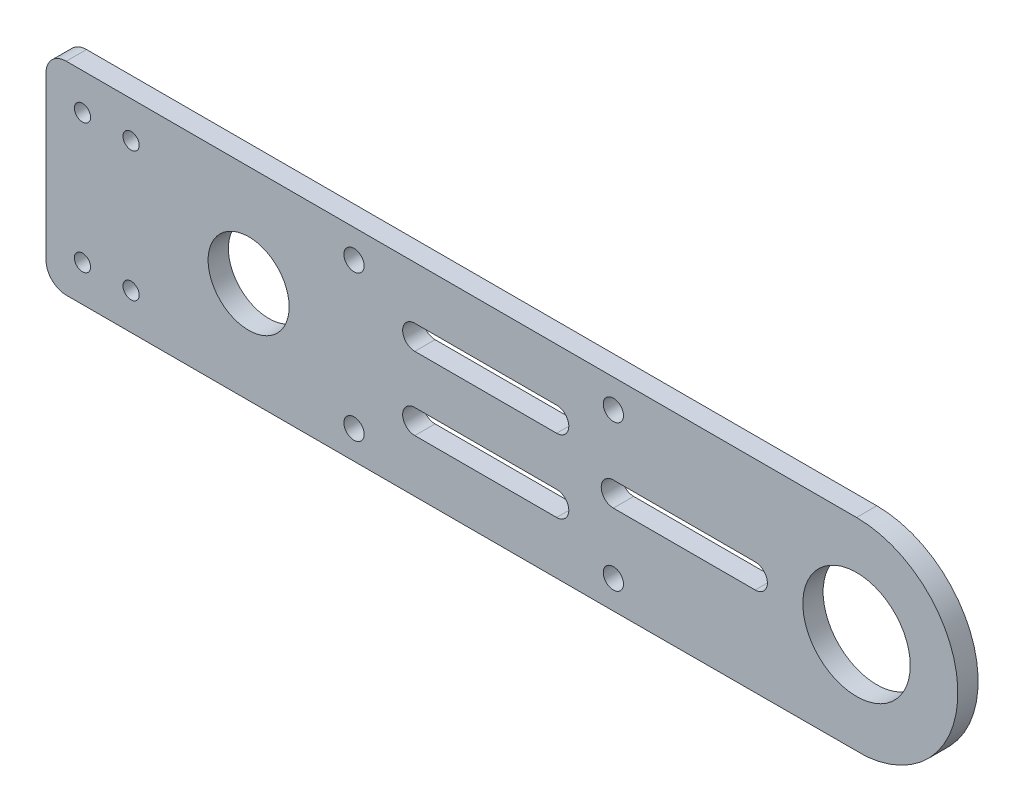
SolidWorks part; units mm, degrees
other "标注1"
sketch "草图2" plane through (-16, 25, 5) normal (-0.2141, 0.5303, 0.8203) x (0.969, 0.0095, 0.2468)
material "6061 合金"
ref_plane "前视基准面" through (0, 0, 0) normal (0, 0, 1) x (1, 0, 0)
ref_plane "上视基准面" through (0, 0, 0) normal (0, 1, 0) x (1, 0, 0)
ref_plane "右视基准面" through (0, 0, 0) normal (1, 0, 0) x (0, 0, -1)
sketch "草图1" plane through (0, 0, 0) normal (0, 0, 1) x (1, 0, 0)
  line L1 (0, 0) -> (184, 0) construction
  line L3 (75, 9) -> (110, 9) construction
  line L4 (0, 25) -> (124.8693, 25)
  line L17 (0, -25) -> (124.8693, -25)
  line L21 (0, 0) -> (5, 0) construction
  line L22 (5, 0) -> (5, 16) construction
  line L23 (124.8693, 25) -> (184, 25)
  line L24 (124.8693, -25) -> (186.4905, -24.8756)
  line L53 (75, 12) -> (110, 12)
  line L54 (75, 6) -> (110, 6)
  line L55 (75, -9) -> (110, -9) construction
  line L56 (75, -12) -> (110, -12)
  line L72 (130.7557, 4.1147) -> (130.7557, 16.1147) construction
  line L73 (130.7557, 16.1147) -> (160.7557, 16.1147) construction
  line L74 (160.7557, 16.1147) -> (130.7557, 4.1147) construction
  line L78 (130.7557, 4.1147) -> (158.292, 4.1147) construction
  line L79 (144.7181, 4.1147) -> (160.7557, 10.5297) construction
  line L80 (144.7181, 4.1147) -> (160.7557, 4.1147) construction
  line L81 (160.7557, 4.1147) -> (160.7557, 10.5297) construction
  line L91 (130.7557, 17.1147) -> (160.7557, 17.1147) construction
  line L92 (129.7557, 16.1147) -> (129.7557, 4.1147) construction
  line L93 (131.1271, 3.1862) -> (161.1271, 15.1862) construction
  line L94 (144.4708, -5.0836) -> (160.5084, -11.4986) construction
  line L95 (144.7181, 3.1147) -> (160.7557, 3.1147) construction
  line L96 (161.7557, 10.5297) -> (161.7557, 4.1147) construction
  line L97 (144.4708, 5.0836) -> (160.5084, 11.4986) construction
  line L98 (161.7557, -10.5297) -> (161.7557, -4.1147) construction
  line L99 (144.7181, -3.1147) -> (160.7557, -3.1147) construction
  line L100 (130.7557, -17.1147) -> (160.7557, -17.1147) construction
  line L101 (131.1271, -3.1862) -> (161.1271, -15.1862) construction
  line L102 (129.7557, -16.1147) -> (129.7557, -4.1147) construction
  line L103 (75, -6) -> (110, -6)
  line L104 (124, 0) -> (159, 0) construction
  line L105 (124, 3) -> (159, 3)
  line L106 (124, -3) -> (159, -3)
  line L107 (0, 25) -> (-16, 25)
  line L108 (-16, 25) -> (-16, -25)
  line L109 (-16, -25) -> (0, -25)
  line L110 (5, 16) -> (-7, 16) construction
  circle A5 centre (184, 0) radius 13.25
  circle A6 centre (184, 0) radius 16 construction
  arc A7 (186.4905, -24.8756) -> (184, 25) centre (184, 0) ccw
  circle A15 centre (5, 16) radius 2
  circle A16 centre (5, -16) radius 2
  circle A35 centre (60, 18) radius 2.5
  circle A36 centre (124, 18) radius 2.5
  circle A39 centre (34, 0) radius 10
  circle A45 centre (124, -18) radius 2.5
  circle A46 centre (60, -18) radius 2.5
  arc A80 (130.7557, 17.1147) -> (129.7557, 16.1147) centre (130.7557, 16.1147) ccw construction
  arc A81 (129.7557, 4.1147) -> (131.1271, 3.1862) centre (130.7557, 4.1147) ccw construction
  arc A82 (161.1271, 15.1862) -> (160.7557, 17.1147) centre (160.7557, 16.1147) ccw construction
  arc A83 (161.7557, 10.5297) -> (160.5084, 11.4986) centre (160.7557, 10.5297) ccw construction
  arc A84 (160.7557, 3.1147) -> (161.7557, 4.1147) centre (160.7557, 4.1147) ccw construction
  arc A85 (144.4708, 5.0836) -> (144.7181, 3.1147) centre (144.7181, 4.1147) ccw construction
  arc A86 (144.4708, -5.0836) -> (144.7181, -3.1147) centre (144.7181, -4.1147) cw construction
  arc A87 (161.7557, -10.5297) -> (160.5084, -11.4986) centre (160.7557, -10.5297) cw construction
  arc A88 (160.7557, -3.1147) -> (161.7557, -4.1147) centre (160.7557, -4.1147) cw construction
  arc A89 (130.7557, -17.1147) -> (129.7557, -16.1147) centre (130.7557, -16.1147) cw construction
  arc A90 (161.1271, -15.1862) -> (160.7557, -17.1147) centre (160.7557, -16.1147) cw construction
  arc A91 (129.7557, -4.1147) -> (131.1271, -3.1862) centre (130.7557, -4.1147) cw construction
  circle A92 centre (184, 16) radius 1.5 construction
  circle A93 centre (200, 0) radius 1.5 construction
  circle A94 centre (184, -16) radius 1.5 construction
  circle A95 centre (168, 0) radius 1.5 construction
  arc A96 (75, 12) -> (75, 6) centre (75, 9) ccw
  arc A97 (110, 6) -> (110, 12) centre (110, 9) ccw
  arc A98 (75, -12) -> (75, -6) centre (75, -9) cw
  arc A99 (110, -6) -> (110, -12) centre (110, -9) cw
  arc A100 (124, 3) -> (124, -3) centre (124, 0) ccw
  arc A101 (159, -3) -> (159, 3) centre (159, 0) ccw
  circle A102 centre (-7, 16) radius 2
  circle A103 centre (-7, -16) radius 2
  point P5 (92.5, 9)
  point P19 (92.5, -9)
  point P32 (141.5, 0)
  point P147 (184, 0)
  dimension "D11" = 3
  dimension "D7" = 25
  dimension "D8" = 200
  dimension "D12" = 50
  dimension "D19" = 2
  dimension "D23" = 2
  dimension "D27" = 25
  dimension "D28" = 2
  dimension "D29" = 2
  dimension "D30" = 2
  dimension "D31" = 2
  dimension "D32" = 4
  dimension "D33" = 150
  dimension "D4" = 9
  dimension "D2" = 25
  dimension "D5" = 18
  dimension "D6" = 16
  dimension "D9" = 15
  dimension "D10" = 35
  dimension "D20" = 18
  dimension "D21" = 60
  dimension "D25" = 12
  dimension "D26" = 30
extrude "凸台-拉伸1" add sketch "草图1" along normal blind 5
fillet "圆角1" radius 5 2 edges at (-16, -25, 2.5) (-16, 25, 2.5)
